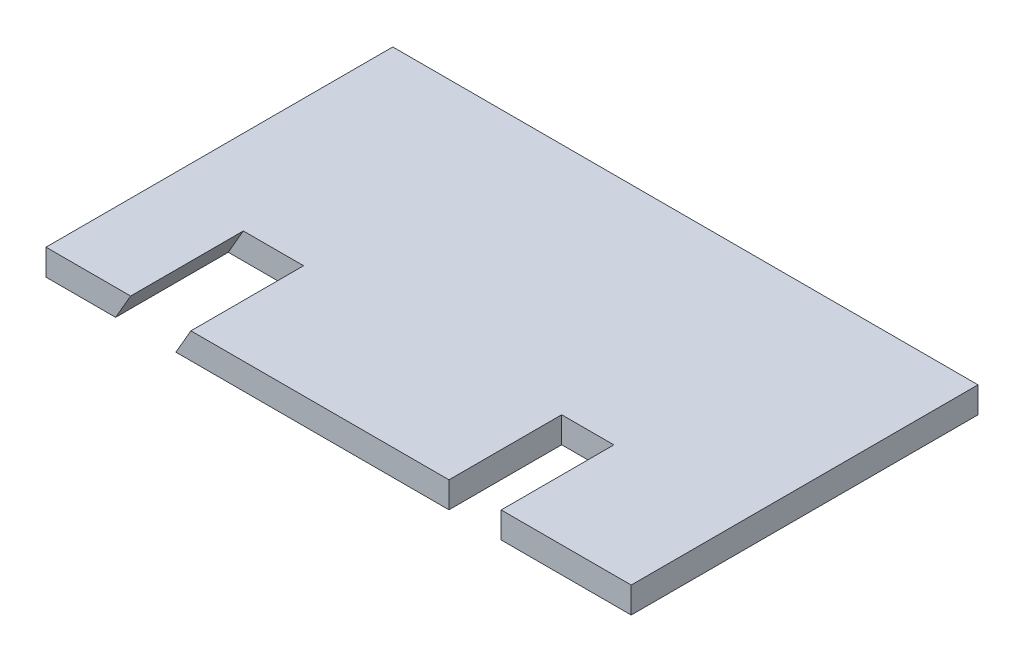
SolidWorks part; units mm, degrees
ref_plane "Front Plane" through (0, 0, 0) normal (0, 0, 1) x (1, 0, 0)
ref_plane "Top Plane" through (0, 0, 0) normal (0, 1, 0) x (1, 0, 0)
ref_plane "Right Plane" through (0, 0, 0) normal (1, 0, 0) x (0, 0, -1)
sketch "Sketch1" plane through (0, 0, 0) normal (0, 0, 1) x (1, 0, 0)
  line L1 (-67.5, 3) -> (67.5, 3)
  line L2 (-67.5, 3) -> (-67.5, -3)
  line L3 (-67.5, -3) -> (67.5, -3)
  line L4 (67.5, 3) -> (67.5, -3)
  line L5 (-67.5, 3) -> (67.5, -3) construction
  line L6 (-67.5, -3) -> (67.5, 3) construction
  point P0 (0, 0)
  dimension "D1" = 135
  dimension "D2" = 6
extrude "Boss-Extrude1" add sketch "Sketch1" along normal blind 80
sketch "Sketch2" plane through (0, 0, 80) normal (0, 0, 1) x (1, 0, 0)
  line L0 (67.5, 3) -> (-67.5, 3) construction
  line L1 (25.46, 3) -> (37.5, 3)
  line L2 (25.46, 3) -> (25.46, -3)
  line L3 (25.46, -3) -> (37.5, -3)
  line L4 (37.5, 3) -> (37.5, -3)
  line L5 (-67.5, -3) -> (67.5, -3) construction
  line L6 (-34.0759, 3) -> (-37.54, -3)
  line L7 (-47.9785, 3) -> (-51.4426, -3)
  line L8 (-47.9785, 3) -> (-34.0759, 3)
  line L9 (-51.4426, -3) -> (-37.54, -3)
  line L10 (67.5, -3) -> (67.5, 3) construction
  line L11 (-40.2966, 16.3055) -> (-54.8826, -8.9583) construction
  line L12 (-29.8696, 10.2855) -> (-44.4557, -14.9783) construction
  point P18 (67.5, 0)
  dimension "D1" = 12.04
  dimension "D2" = 60
  dimension "D4" = 63
  dimension "D5" = 30
  dimension "D3" = 12.04
extrude "Cut-Extrude1" cut sketch "Sketch2" against normal blind 26
